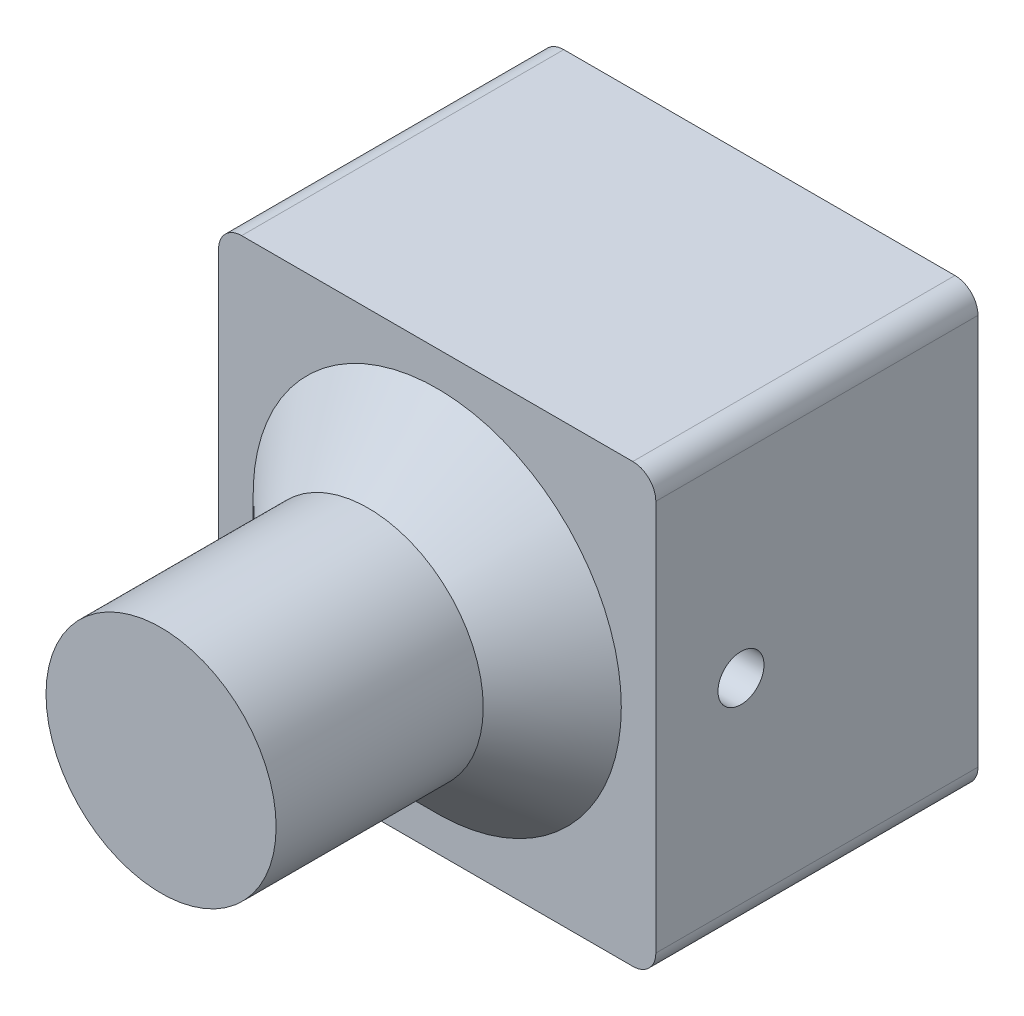
SolidWorks part; units mm, degrees
ref_plane "Front Plane" through (0, 0, 0) normal (0, 0, 1) x (1, 0, 0)
ref_plane "Top Plane" through (0, 0, 0) normal (0, 1, 0) x (1, 0, 0)
ref_plane "Right Plane" through (0, 0, 0) normal (1, 0, 0) x (0, 0, -1)
sketch "Sketch1" plane through (0, 0, 0) normal (0, 0, 1) x (1, 0, 0)
  line L1 (56.7274, 61.4616) -> (75.7274, 61.4616)
  line L2 (56.7274, 61.4616) -> (56.7274, 42.4616)
  line L3 (56.7274, 42.4616) -> (75.7274, 42.4616)
  line L4 (75.7274, 61.4616) -> (75.7274, 42.4616)
  dimension "D1" = 19
  dimension "D2" = 19
extrude "Boss-Extrude1" add sketch "Sketch1" along normal blind 14
fillet "Fillet1" radius 1 4 edges at (75.7274, 42.4616, 7) (56.7274, 42.4616, 7) (75.7274, 61.4616, 7) (56.7274, 61.4616, 7)
sketch "Sketch2" plane through (0, 0, 14) normal (0, 0, 1) x (1, 0, 0)
  circle A0 centre (66.2274, 51.9616) radius 5
extrude "Boss-Extrude2" add sketch "Sketch2" along normal blind 12
chamfer "Chamfer1" distance 3 angle 45 1 edges at (71.2274, 51.9616, 14)
sketch "Sketch3" plane through (56.7274, 0, 0) normal (-1, 0, 0) x (0, 0, 1)
  line L0 (0, 60.4616) -> (0, 43.4616) construction
  circle A0 centre (10.3, 51.9616) radius 1
  dimension "D1" = 2
  dimension "D2" = 10.3
extrude "Cut-Extrude1" cut sketch "Sketch3" against normal blind 5
sketch "Sketch4" plane through (75.7274, 0, 0) normal (1, 0, 0) x (0, 0, -1)
  circle A1 centre (-10.3, 51.9616) radius 1
  circle A2 centre (-10.3, 51.9616) radius 1
  dimension "D1" = 0
extrude "Cut-Extrude2" cut sketch "Sketch4" against normal blind 5
